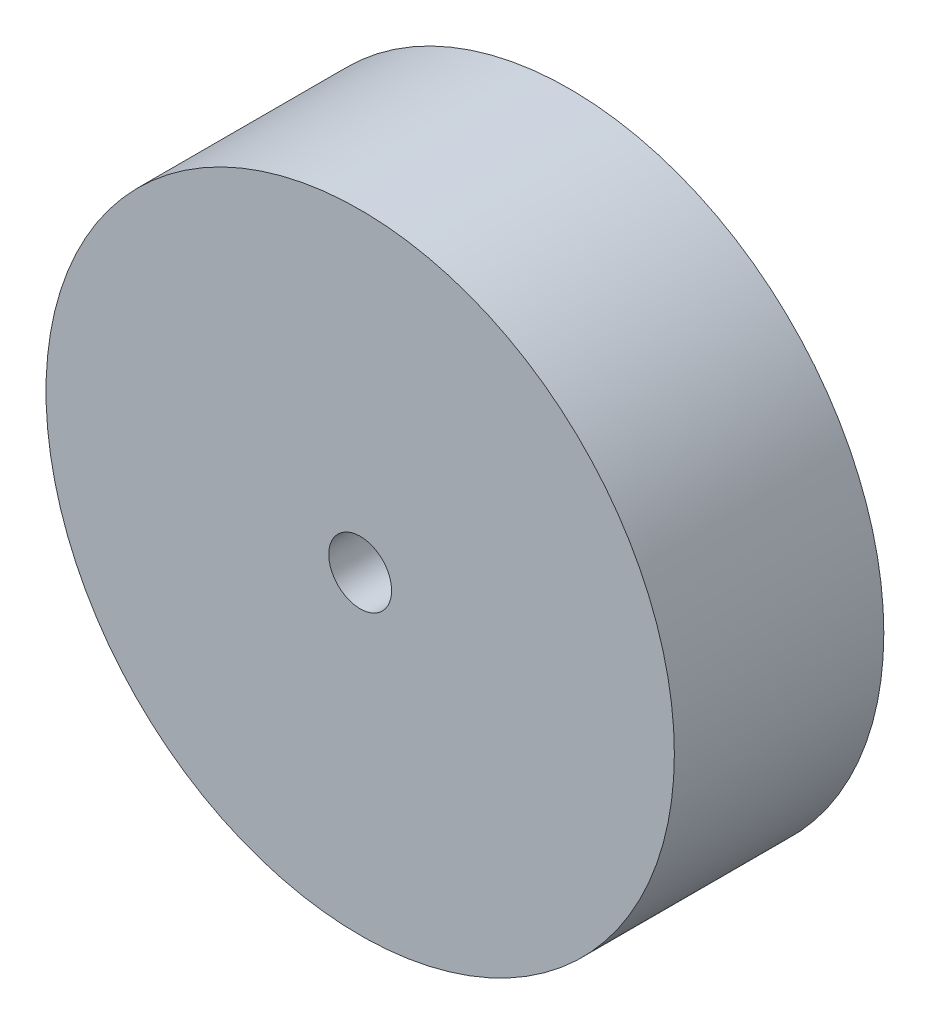
SolidWorks part; units mm, degrees
ref_plane "前视基准面" through (0, 0, 0) normal (0, 0, 1) x (1, 0, 0)
ref_plane "上视基准面" through (0, 0, 0) normal (0, 1, 0) x (1, 0, 0)
ref_plane "右视基准面" through (0, 0, 0) normal (1, 0, 0) x (0, 0, -1)
other "Configuration Table"
sketch "草图1" plane through (0, 0, 0) normal (0, 0, 1) x (1, 0, 0)
  circle A0 centre (0, 0) radius 15
  circle A1 centre (0, 0) radius 1.5
extrude "凸台-拉伸2" add sketch "草图1" along normal blind 10
